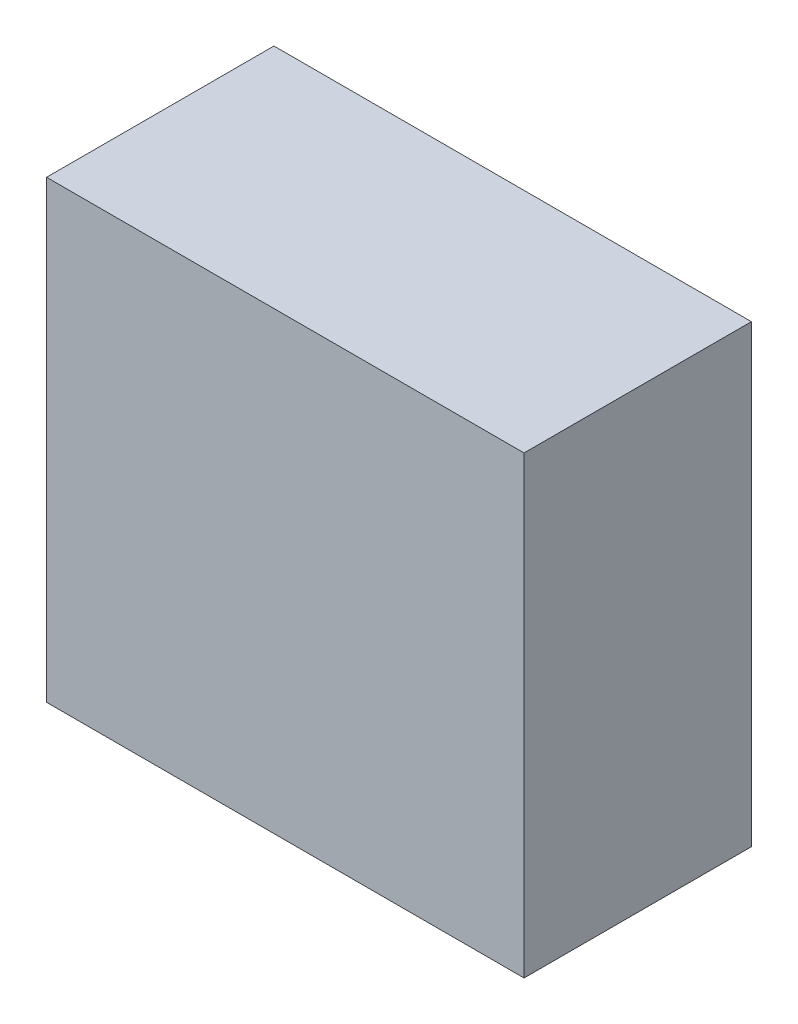
SolidWorks part; units mm, degrees
ref_plane "Front Plane" through (0, 0, 0) normal (0, 0, 1) x (1, 0, 0)
ref_plane "Top Plane" through (0, 0, 0) normal (0, 1, 0) x (1, 0, 0)
ref_plane "Right Plane" through (0, 0, 0) normal (1, 0, 0) x (0, 0, -1)
sketch "Sketch1" plane through (0, 0, 0) normal (0, 0, 1) x (1, 0, 0)
  line L1 (0, 0) -> (21, 0)
  line L2 (0, 0) -> (0, 20)
  line L3 (0, 20) -> (21, 20)
  line L4 (21, 0) -> (21, 20)
  dimension "D1" = 21
  dimension "D2" = 20
extrude "Boss-Extrude1" add sketch "Sketch1" along normal blind 10
